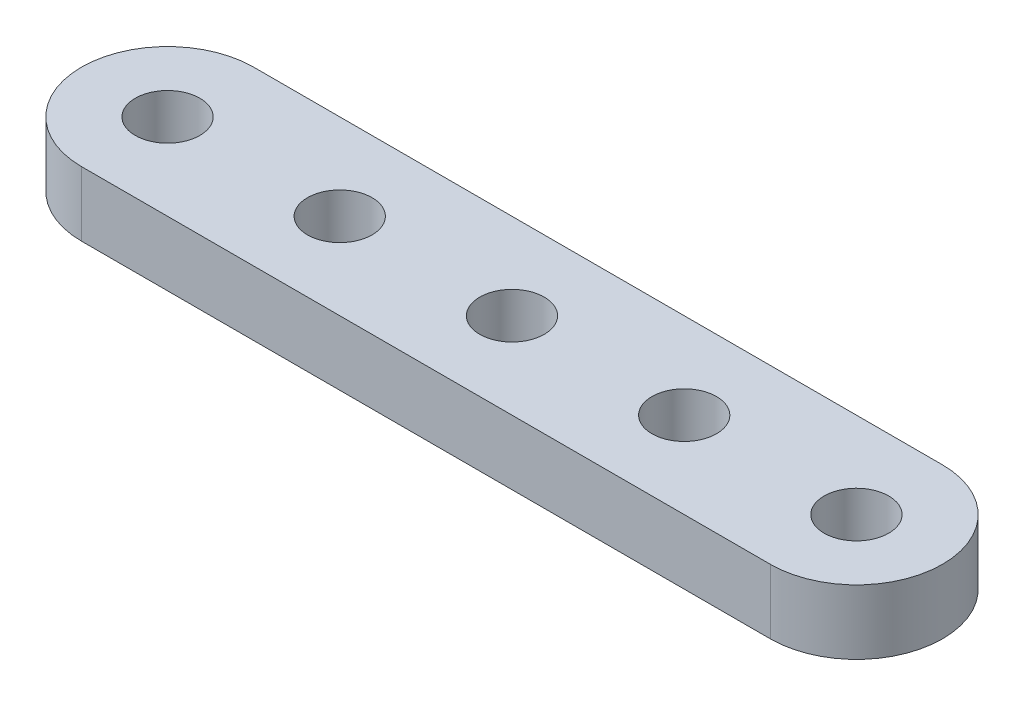
SolidWorks part; units mm, degrees
ref_plane "Front Plane" through (0, 0, 0) normal (0, 0, 1) x (1, 0, 0)
ref_plane "Top Plane" through (0, 0, 0) normal (0, 1, 0) x (1, 0, 0)
ref_plane "Right Plane" through (0, 0, 0) normal (1, 0, 0) x (0, 0, -1)
sketch "Sketch2" plane through (0, 0, 0) normal (0, 1, 0) x (1, 0, 0)
  line L0 (0, 0) -> (32, 0) construction
  line L1 (0, 4) -> (32, 4)
  line L2 (0, -4) -> (32, -4)
  arc A0 (0, 4) -> (0, -4) centre (0, 0) ccw
  arc A1 (32, -4) -> (32, 4) centre (32, 0) ccw
  circle A2 centre (0, 0) radius 1.5
  circle A3 centre (8, 0) radius 1.5
  circle A4 centre (16, 0) radius 1.5
  circle A5 centre (24, 0) radius 1.5
  circle A6 centre (32, 0) radius 1.5
  circle A7 centre (40, 0) radius 1.5
  circle A8 centre (48, 0) radius 1.5
  circle A9 centre (56, 0) radius 1.5
  circle A10 centre (64, 0) radius 1.5
  circle A11 centre (72, 0) radius 1.5
  circle A12 centre (80, 0) radius 1.5
  point P3 (16, 0)
  dimension "D1" = 3
  dimension "D2" = 8
  dimension "D3" = 32
  dimension "D4" = 11
extrude "Boss-Extrude2" add sketch "Sketch2" along normal blind 3
sketch "Sketch3" plane through (0, 0, 0) normal (0, -1, 0) x (-1, 0, 0)
  line L1 (-37.2739, -4.6196) -> (-85.7282, -4.6196)
  line L2 (-37.2739, -4.6196) -> (-37.2739, 3.1279)
  line L3 (-37.2739, 3.1279) -> (-85.7282, 3.1279)
  line L4 (-85.7282, -4.6196) -> (-85.7282, 3.1279)
extrude "Cut-Extrude1" cut sketch "Sketch3" against normal blind 10
